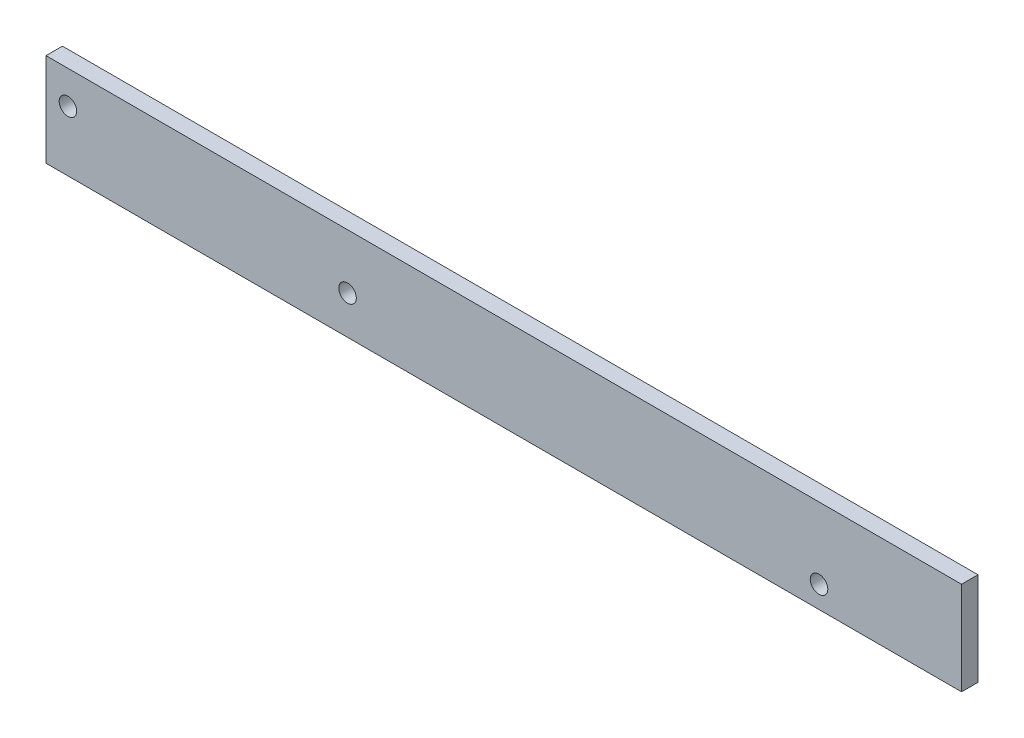
SolidWorks part; units mm, degrees
ref_plane "Plan de face" through (0, 0, 0) normal (0, 0, 1) x (1, 0, 0)
ref_plane "Plan de dessus" through (0, 0, 0) normal (0, 1, 0) x (1, 0, 0)
ref_plane "Plan de droite" through (0, 0, 0) normal (1, 0, 0) x (0, 0, -1)
sketch "Esquisse1" plane through (0, 0, 0) normal (0, 0, 1) x (1, 0, 0)
  line L0 (-65.5, -11.5) -> (-65.5, -8.5) construction
  line L1 (101.5, -8.5) -> (-65.5, -8.5)
  line L2 (101.5, -8.5) -> (101.5, 8.5)
  line L3 (101.5, 8.5) -> (-65.5, 8.5)
  line L4 (-65.5, -8.5) -> (-65.5, 8.5)
  line L5 (101.5, 104.5) -> (101.5, -8.5) construction
  point P0 (0, 0)
  dimension "D1" = 17
extrude "Boss.-Extru.1" add sketch "Esquisse1" along normal blind 3
sketch "Sketch1" plane through (0, 0, 3) normal (0, 0, 1) x (1, 0, 0)
  circle A0 centre (-61.5, 2.5) radius 1.6
extrude "Cut-Extrude1" cut sketch "Sketch1" against normal through all
sketch "Sketch2" plane through (0, 0, 0) normal (0, 0, -1) x (-1, 0, 0)
  circle A0 centre (-75.5, -4.5) radius 1.6
extrude "Cut-Extrude2" cut sketch "Sketch2" against normal through all
sketch "Sketch3" plane through (0, 0, 3) normal (0, 0, 1) x (1, 0, 0)
  circle A0 centre (-10.5, -1.5) radius 1.6
extrude "Cut-Extrude3" cut sketch "Sketch3" against normal through all
